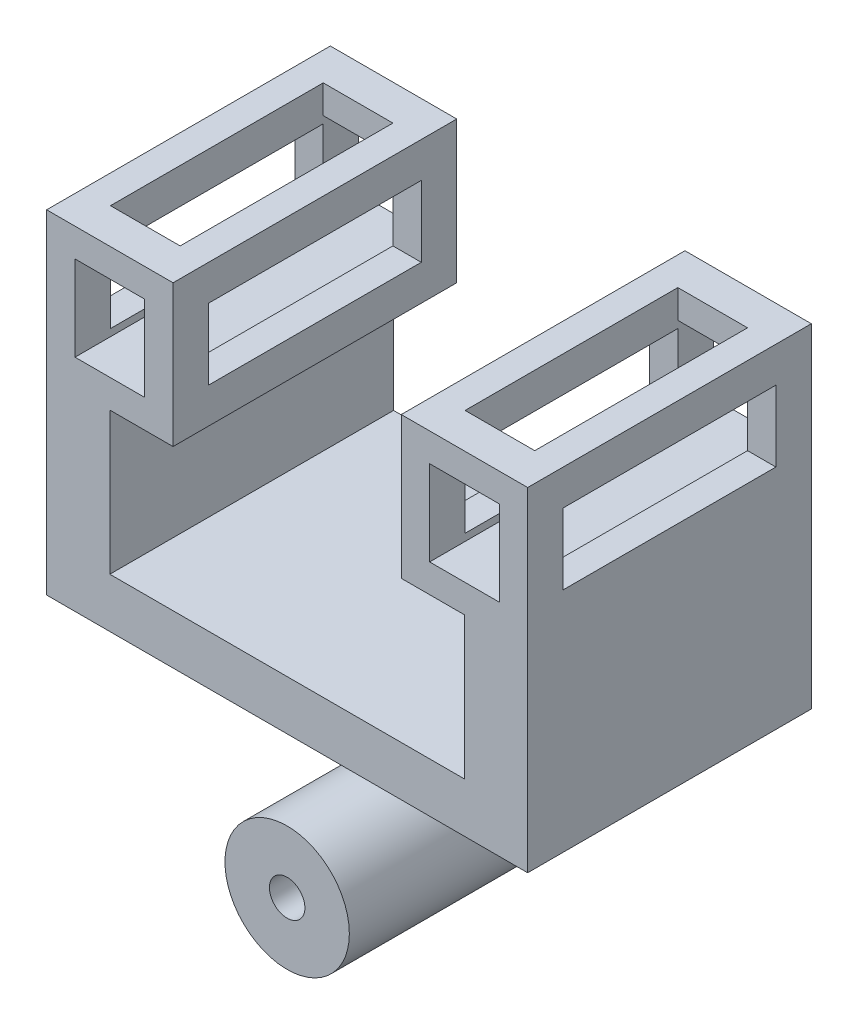
SolidWorks part; units mm, degrees
material "ASTM A36 Steel"
ref_plane "Front Plane" through (0, 0, 0) normal (0, 0, 1) x (1, 0, 0)
ref_plane "Top Plane" through (0, 0, 0) normal (0, 1, 0) x (1, 0, 0)
ref_plane "Right Plane" through (0, 0, 0) normal (1, 0, 0) x (0, 0, -1)
sketch "Sketch1" plane through (0, 0, 0) normal (0, 0, 1) x (1, 0, 0)
  line L0 (-11.1361, 0) -> (-11.1361, 25.4)
  line L1 (-11.1361, 25.4) -> (11.1361, 25.4)
  line L2 (11.1361, 25.4) -> (11.1361, 0)
  arc A0 (11.1361, 0) -> (-11.1361, 0) centre (0, 0) ccw
  arc A1 (11.1361, 0) -> (-11.1361, 0) centre (0, 0) ccw
  dimension "D1" = 22.2722
  dimension "D2" = 25.4
extrude "Boss-Extrude1" add sketch "Sketch1" along normal blind 2.5218 contours A1 L0 L1 L2
sketch "Sketch2" plane through (0, 0, 0) normal (0, 0, 1) x (1, 0, 0)
  circle A0 centre (0, 0) radius 11.1361
  dimension "D1" = 22.2722
extrude "Boss-Extrude2" add sketch "Sketch2" along normal blind 50.8
sketch "Sketch3" plane through (0, 0, 0) normal (0, 0, 1) x (1, 0, 0)
  line L0 (-43.0685, 25.4) -> (43.0685, 25.4)
  line L1 (43.0685, 25.4) -> (43.0685, 85.1481)
  line L2 (43.0685, 85.1481) -> (-43.0685, 85.1481)
  line L3 (-43.0685, 85.1481) -> (-43.0685, 25.4)
  point P3 (0, 25.4)
  dimension "D1" = 86.137
  dimension "D2" = 59.7481
extrude "Boss-Extrude3" add sketch "Sketch3" along normal blind 50.8
sketch "Sketch4" plane through (0, 0, 50.8) normal (0, 0, 1) x (1, 0, 0)
  line L0 (20.4315, 85.1481) -> (20.4315, 59.7481)
  line L1 (43.0685, 85.1481) -> (-43.0685, 85.1481) construction
  line L2 (20.4315, 59.7481) -> (31.75, 59.7481)
  line L3 (31.75, 59.7481) -> (31.75, 34.29)
  line L4 (31.75, 34.29) -> (-31.75, 34.29)
  line L5 (-31.75, 34.29) -> (-31.75, 59.7481)
  line L6 (-31.75, 59.7481) -> (-20.4315, 59.7481)
  line L7 (-20.4315, 59.7481) -> (-20.4315, 85.1481)
  line L8 (-20.4315, 85.1481) -> (20.4315, 85.1481)
  line L9 (43.0685, 25.4) -> (43.0685, 85.1481) construction
  line L10 (-43.0685, 85.1481) -> (-43.0685, 25.4) construction
  line L12 (-43.0685, 25.4) -> (43.0685, 25.4) construction
  dimension "D1" = 22.637
  dimension "D2" = 11.3185
  dimension "D3" = 11.3185
  dimension "D4" = 22.637
  dimension "D6" = 25.4
  dimension "D7" = 25.4
  dimension "D5" = 8.89
extrude "Cut-Extrude1" cut sketch "Sketch4" against normal through all contours L8 L0 L2 L3 L4 L5 L6 L7
ref_plane "Plane1" through (0, 0, 12.7) normal (0, 0, -1) x (-1, 0, 0)
mirror "Mirror1" about plane through (0, 0, 12.7) normal (0, 0, -1) of "Boss-Extrude1"
sketch "Sketch6" plane through (0, 0, 50.8) normal (0, 0, 1) x (1, 0, 0)
  circle A0 centre (0, 0) radius 3.175
  dimension "D1" = 6.35
extrude "Cut-Extrude2" cut sketch "Sketch6" against normal up to next
sketch "Sketch8" plane through (-20.4315, 0, 0) normal (1, 0, 0) x (0, 0, -1)
  line L0 (-50.8, 72.4481) -> (0, 72.4481) construction
  line L1 (-50.8, 59.7481) -> (-50.8, 85.1481) construction
  line L2 (0, 59.7481) -> (0, 85.1481) construction
  line L3 (0, 85.1481) -> (-50.8, 85.1481) construction
  line L4 (-44.45, 66.0981) -> (-6.35, 66.0981)
  line L5 (-44.45, 66.0981) -> (-44.45, 78.7981)
  line L6 (-44.45, 78.7981) -> (-6.35, 78.7981)
  line L7 (-6.35, 66.0981) -> (-6.35, 78.7981)
  line L8 (-44.45, 66.0981) -> (-6.35, 78.7981) construction
  line L9 (-44.45, 78.7981) -> (-6.35, 66.0981) construction
  point P7 (-25.4, 72.4481)
  dimension "D1" = 6.35
  dimension "D2" = 6.35
extrude "Cut-Extrude3" cut sketch "Sketch8" against normal through all both and the other way through all
sketch "Sketch9" plane through (0, 85.1481, 0) normal (0, 1, 0) x (1, 0, 0)
  line L0 (-31.75, 0) -> (-31.75, -50.8) construction
  line L1 (-20.4315, 0) -> (-43.0685, 0) construction
  line L2 (-20.4315, -50.8) -> (-43.0685, -50.8) construction
  line L3 (31.75, 0) -> (31.75, -50.8) construction
  line L4 (-37.9885, -44.45) -> (-25.5115, -44.45)
  line L5 (-37.9885, -44.45) -> (-37.9885, -6.35)
  line L6 (-37.9885, -6.35) -> (-25.5115, -6.35)
  line L7 (-25.5115, -44.45) -> (-25.5115, -6.35)
  line L8 (-37.9885, -44.45) -> (-25.5115, -6.35) construction
  line L9 (-37.9885, -6.35) -> (-25.5115, -44.45) construction
  line L10 (43.0685, 0) -> (20.4315, 0) construction
  line L11 (43.0685, -50.8) -> (20.4315, -50.8) construction
  line L12 (-43.0685, -50.8) -> (-43.0685, 0) construction
  line L13 (25.5115, -44.45) -> (37.9885, -44.45)
  line L14 (25.5115, -44.45) -> (25.5115, -6.35)
  line L15 (25.5115, -6.35) -> (37.9885, -6.35)
  line L16 (37.9885, -44.45) -> (37.9885, -6.35)
  line L17 (25.5115, -44.45) -> (37.9885, -6.35) construction
  line L18 (25.5115, -6.35) -> (37.9885, -44.45) construction
  line L19 (43.0685, -50.8) -> (43.0685, 0) construction
  point P6 (-31.75, -25.4)
  point P17 (31.75, -25.4)
  dimension "D1" = 6.35
  dimension "D2" = 5.08
  dimension "D3" = 6.35
  dimension "D4" = 5.08
extrude "Cut-Extrude4" cut sketch "Sketch9" against normal up to next and the other way through all
sketch "Sketch10" plane through (0, 0, 50.8) normal (0, 0, 1) x (1, 0, 0)
  line L0 (-31.75, 85.1481) -> (-31.75, 59.7481) construction
  line L1 (-20.4315, 85.1481) -> (-43.0685, 85.1481) construction
  line L2 (31.75, 85.1481) -> (31.75, 59.7481) construction
  line L3 (43.0685, 85.1481) -> (20.4315, 85.1481) construction
  line L4 (-20.4315, 59.7481) -> (-20.4315, 85.1481) construction
  line L5 (-37.9885, 64.8281) -> (-25.5115, 64.8281)
  line L6 (-37.9885, 64.8281) -> (-37.9885, 80.0681)
  line L7 (-37.9885, 80.0681) -> (-25.5115, 80.0681)
  line L8 (-25.5115, 64.8281) -> (-25.5115, 80.0681)
  line L9 (-37.9885, 64.8281) -> (-25.5115, 80.0681) construction
  line L10 (-37.9885, 80.0681) -> (-25.5115, 64.8281) construction
  line L11 (25.5115, 64.8281) -> (37.9885, 64.8281)
  line L12 (25.5115, 64.8281) -> (25.5115, 80.0681)
  line L13 (25.5115, 80.0681) -> (37.9885, 80.0681)
  line L14 (37.9885, 64.8281) -> (37.9885, 80.0681)
  line L15 (25.5115, 64.8281) -> (37.9885, 80.0681) construction
  line L16 (25.5115, 80.0681) -> (37.9885, 64.8281) construction
  line L17 (43.0685, 25.4) -> (43.0685, 85.1481) construction
  point P10 (-31.75, 72.4481)
  point P15 (31.75, 72.4481)
  dimension "D1" = 5.08
  dimension "D2" = 5.08
  dimension "D3" = 5.08
  dimension "D4" = 5.08
extrude "Cut-Extrude5" cut sketch "Sketch10" against normal through all
equation "\"F\"= 600'Applied Load [lbf]"
equation "\"P\"= \"F\" / 2'Symmetric Leg Force [lbf]"
equation "\"Ys\"= 36259.43'Material Yield Strength (ASTM A36) [psi]"
equation "\"E\"= 29007547.53'Elastic Modulus (ASTM A36) [psi]"
equation "\"Ns\"= 4'Factor of Safety"
equation "\"sigma_allow\"= \"Ys\" / \"Ns\"'Allowable Bending/Tensile Stress [psi]"
equation "\"delta_max\"= 0.005'Maximum Deflection Limit [in]"
equation "\"L_A\"= 2.00'Feature A Pin Length [in]"
equation "\"d_stress_A\"= ( ( 32 * \"P\" * \"L_A\" ) / ( pi * \"sigma_allow\" ) ) ^ ( 1 / 3 )'Feature A Minimum Stress Diameter [in]"
equation "\"d_stiff_A\"= ( ( 64 * \"P\" * ( \"L_A\" ^ 3 ) ) / ( 3 * pi * \"E\" * \"delta_max\" ) ) ^ ( 1 / 4 )'Feature A Minimum Stiffness Diameter [in]"
equation "\"d_A\"= 1.000'Feature A Selected Nominal Diameter [in]"
equation "\"w_B\"= \"d_A\"'Feature B Width (Tied to Feature A Pin Dia) [in]"
equation "\"L_B\"= 2.00'Feature B Link Length [in]"
equation "\"t_stress_B\"= \"P\" / ( \"w_B\" * \"sigma_allow\" )'Feature B Minimum Tensile Thickness [in]"
equation "\"t_stiff_B\"= ( \"P\" * \"L_B\" ) / ( \"w_B\" * \"E\" * \"delta_max\" )'Feature B Minimum Stiffness Thickness [in]"
equation "\"t_B\"= 0.250'Feature B Selected Nominal Thickness [in]"
equation "\"L_C\"= 2.5'Feature C Beam Span Length [in]"
equation "\"w_C\"= 1.00'Feature C Beam Cross-Section Width [in]"
equation "\"h_stress_C\"= ( ( 1.5 * \"P\" * \"L_C\" ) / ( \"w_C\" * \"sigma_allow\" ) ) ^ ( 1 / 2 )'Feature C Minimum Bending Height [in]"
equation "\"h_stiff_C\"= ( ( \"P\" * ( \"L_C\" ^ 3 ) ) / ( 4 * \"w_C\" * \"E\" * \"delta_max\" ) ) ^ ( 1 / 3 )'Feature C Minimum Stiffness Height [in]"
equation "\"h_C\"= 0.375'Feature C Selected Nominal Height [in]"
equation "\"P_D\"= \"P\" / 2'Feature D Reaction Load from Feature C [lbf]"
equation "\"L_D\"= 2.00'Feature D Web Cantilever Length [in]"
equation "\"w_D\"= 1.00'Feature D Web Width [in]"
equation "\"t_stress_D\"= ( ( 6 * \"P_D\" * \"L_D\" ) / ( \"w_D\" * \"sigma_allow\" ) ) ^ ( 1 / 2 )'Feature D Minimum Bending Thickness [in]"
equation "\"t_stiff_D\"= ( ( 4 * \"P_D\" * ( \"L_D\" ^ 3 ) ) / ( \"w_D\" * \"E\" * \"delta_max\" ) ) ^ ( 1 / 3 )'Feature D Minimum Stiffness Thickness [in]"
equation "\"t_D\"= 0.500'Feature D Selected Nominal Thickness [in]"
equation "\"P_E\"= \"P_D\"'Feature E Transferred Flange Load [lbf]"
equation "\"L_E\"= 2.00'Feature E Flange Overhang Span [in]"
equation "\"w_E\"= 1.00'Feature E Flange Width [in]"
equation "\"h_stress_E\"= ( ( 6 * \"P_E\" * \"L_E\" ) / ( \"w_E\" * \"sigma_allow\" ) ) ^ ( 1 / 2 )'Feature E Minimum Bending Thickness [in]"
equation "\"h_stiff_E\"= ( ( 4 * \"P_E\" * ( \"L_E\" ^ 3 ) ) / ( \"w_E\" * \"E\" * \"delta_max\" ) ) ^ ( 1 / 3 )'Feature E Minimum Stiffness Thickness [in]"
equation "\"h_E\"= 0.500'Feature E Selected Nominal Thickness [in]"
equation "\"D1@Sketch1\"=\"d_stress_A\""
equation "\"D1@Boss-Extrude1\"=\"t_stress_B\"*3"
equation "\"D1@Sketch2\"=\"d_stress_A\""
equation "\"D1@Boss-Extrude2\"=\"L_A\""
equation "\"D1@Sketch3\"=\"L_C\"+2*(\"t_stress_D\")"
equation "\"D2@Sketch3\"=\"h_stress_C\" + \"w_D\"+\"w_E\""
equation "\"D7@Sketch4\"=\"w_E\""
equation "\"D6@Sketch4\"=\"w_E\""
equation "\"D1@Sketch4\"=\"t_stress_D\"+\"h_stress_E\""
equation "\"D4@Sketch4\"=\"t_stress_D\"+\"h_stress_E\""
equation "\"D2@Sketch4\"=\"t_stress_D\""
equation "\"D3@Sketch4\"=\"t_stress_D\""
equation "\"D1@Boss-Extrude3\"=\"L_D\""
